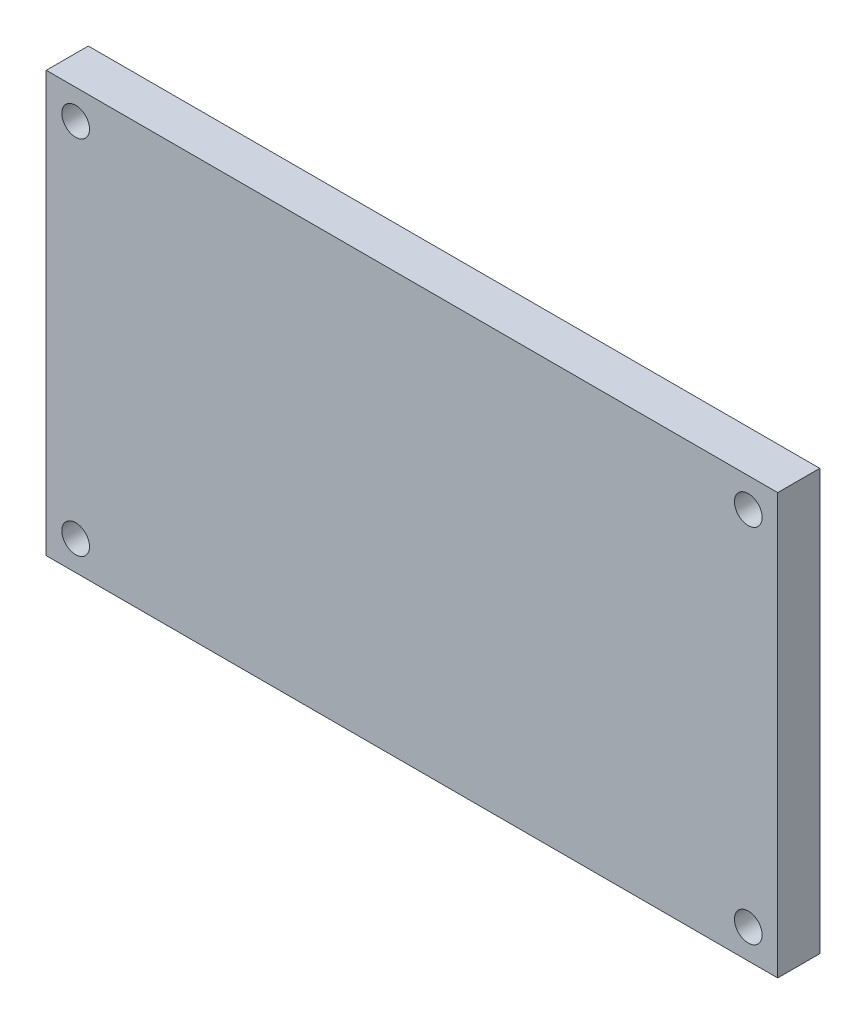
SolidWorks part; units mm, degrees
ref_plane "前视基准面" through (0, 0, 0) normal (0, 0, 1) x (1, 0, 0)
ref_plane "上视基准面" through (0, 0, 0) normal (0, 1, 0) x (1, 0, 0)
ref_plane "右视基准面" through (0, 0, 0) normal (1, 0, 0) x (0, 0, -1)
other "Configuration Table"
sketch "草图1" plane through (0, 0, 0) normal (0, 0, 1) x (1, 0, 0)
  line L1 (-43.5, -25) -> (43.5, -25)
  line L2 (-43.5, -25) -> (-43.5, 25)
  line L3 (-43.5, 25) -> (43.5, 25)
  line L4 (43.5, -25) -> (43.5, 25)
  line L5 (-43.5, -25) -> (43.5, 25) construction
  line L6 (-43.5, 25) -> (43.5, -25) construction
  line L7 (-40, -21.5) -> (40, -21.5) construction
  line L8 (-40, -21.5) -> (-40, 21.5) construction
  line L9 (-40, 21.5) -> (40, 21.5) construction
  line L10 (40, -21.5) -> (40, 21.5) construction
  line L11 (-40, -21.5) -> (40, 21.5) construction
  line L12 (-40, 21.5) -> (40, -21.5) construction
  circle A0 centre (40, 21.5) radius 1.65
  circle A1 centre (40, -21.5) radius 1.65
  circle A2 centre (-40, 21.5) radius 1.65
  circle A3 centre (-40, -21.5) radius 1.65
  point P0 (0, 0)
  point P6 (0, 0)
  dimension "D5" = 3.3
  dimension "D6" = 3.3
  dimension "D7" = 3.3
  dimension "D8" = 3.3
  dimension "D1" = 50
  dimension "D2" = 87
  dimension "D3" = 80
  dimension "D4" = 43
extrude "凸台-拉伸1" add sketch "草图1" along normal blind 5
